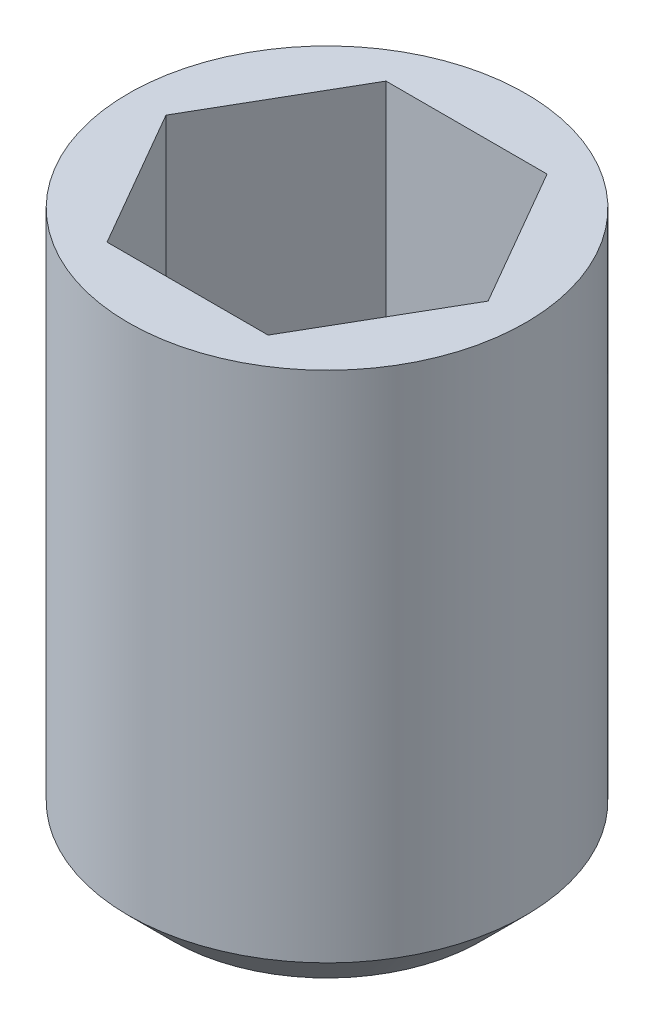
SolidWorks part; units mm, degrees
material "Cast Alloy Steel"
ref_plane "Front Plane" through (0, 0, 0) normal (0, 0, 1) x (1, 0, 0)
ref_plane "Top Plane" through (0, 0, 0) normal (0, 1, 0) x (1, 0, 0)
ref_plane "Right Plane" through (0, 0, 0) normal (1, 0, 0) x (0, 0, -1)
sketch "Sketch1" plane through (0, 0, 0) normal (0, 1, 0) x (1, 0, 0)
  circle A0 centre (0, 0) radius 1.1303
  dimension "D1" = 2.2606
extrude "Boss-Extrude1" add sketch "Sketch1" against normal blind 3.175
chamfer "Chamfer1" distance 0.254 angle 45 1 edges at (0, -3.175, 1.1303)
dome "Dome1" [suppressed] faces to dome 1 distance 0.508 parameters "D1"=0.508
sketch "Sketch2" plane through (0, 0, 0) normal (0, 1, 0) x (1, 0, 0)
  line L1 (-0.9165, 0) -> (-0.4583, -0.7937)
  line L2 (-0.4583, -0.7937) -> (0.4583, -0.7937)
  line L3 (0.4583, -0.7937) -> (0.9165, 0)
  line L4 (0.9165, 0) -> (0.4583, 0.7938)
  line L5 (0.4583, 0.7938) -> (-0.4583, 0.7938)
  line L6 (-0.4583, 0.7938) -> (-0.9165, 0)
  circle A0 centre (0, 0) radius 0.7937 construction
  dimension "D1" = 1.5875
extrude "Cut-Extrude1" cut sketch "Sketch2" against normal blind 1.27
